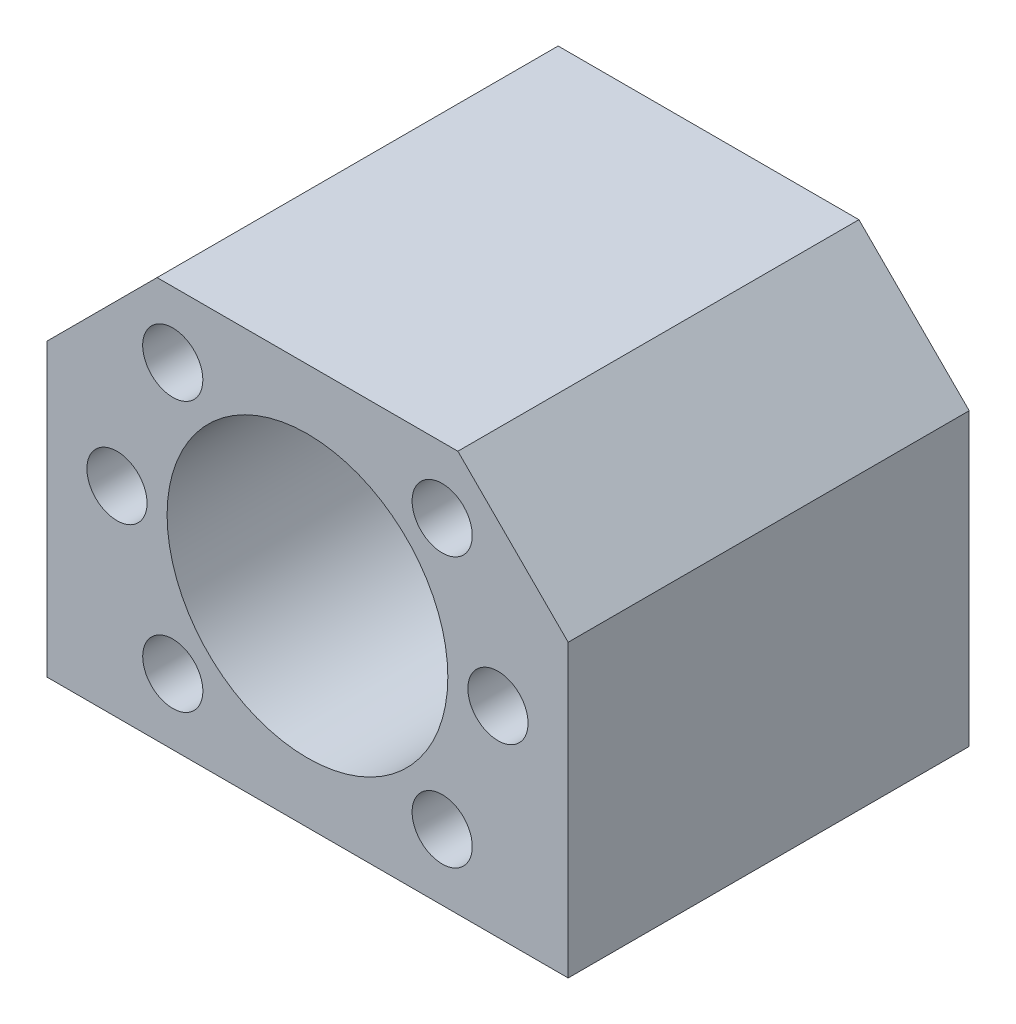
SolidWorks part; units mm, degrees
ref_plane "Plan de face" through (0, 0, 0) normal (0, 0, 1) x (1, 0, 0)
ref_plane "Plan de dessus" through (0, 0, 0) normal (0, 1, 0) x (1, 0, 0)
ref_plane "Plan de droite" through (0, 0, 0) normal (1, 0, 0) x (0, 0, -1)
sketch "Esquisse1" plane through (0, 0, 0) normal (0, 0, 1) x (1, 0, 0)
  line L1 (0, 0) -> (52, 0)
  line L2 (0, 0) -> (0, 40)
  line L3 (0, 40) -> (52, 40)
  line L4 (52, 0) -> (52, 40)
  dimension "D1" = 52
  dimension "D2" = 40
extrude "Boss.-Extru.1" add sketch "Esquisse1" along normal blind 40
sketch "Esquisse2" plane through (0, 0, 40) normal (0, 0, 1) x (1, 0, 0)
  line L0 (26, 0) -> (26, 40) construction
  line L1 (0, 0) -> (52, 0) construction
  line L2 (52, 40) -> (0, 40) construction
  circle A0 centre (26, 20) radius 14
  dimension "D1" = 28
extrude "Enlèv. mat.-Extru.1" cut sketch "Esquisse2" against normal up to vertex (40 mm away) up to point (52, 0, 0)
sketch "Esquisse3" plane through (0, 0, 40) normal (0, 0, 1) x (1, 0, 0)
  line L0 (0, 20) -> (52, 20) construction
  line L1 (0, 40) -> (0, 0) construction
  line L2 (52, 0) -> (52, 40) construction
  line L3 (26, 40) -> (26, 0) construction
  line L4 (52, 40) -> (0, 40) construction
  line L5 (0, 0) -> (52, 0) construction
  line L6 (26, 20) -> (12.565, 33.435) construction
  circle A0 centre (7, 20) radius 3
  circle A1 centre (12.565, 33.435) radius 3
  arc A2 (7, 20) -> (12.565, 33.435) centre (26, 20) cw construction
  circle A3 centre (12.565, 6.565) radius 3
  arc A4 (45, 20) -> (39.435, 33.435) centre (26, 20) ccw construction
  circle A5 centre (39.435, 6.565) radius 3
  circle A6 centre (39.435, 33.435) radius 3
  circle A7 centre (45, 20) radius 3
  dimension "D1" = 6
  dimension "D2" = 38
  dimension "D3" = 45
extrude "Enlèv. mat.-Extru.2" cut sketch "Esquisse3" against normal blind 10
chamfer "Chanfrein1" distance 11 angle 45 2 edges at (0, 40, 20) (52, 40, 20)
sketch "Esquisse4" plane through (0, 0, 0) normal (0, -1, 0) x (1, 0, 0)
  line L0 (26, 0) -> (26, 40) construction
  line L1 (0, 0) -> (52, 0) construction
  line L2 (0, 40) -> (52, 40) construction
  line L3 (0, 20) -> (52, 20) construction
  line L4 (0, 40) -> (0, 0) construction
  line L5 (52, 40) -> (52, 0) construction
  circle A0 centre (6, 32) radius 3
  circle A1 centre (6, 8) radius 3
  circle A2 centre (46, 8) radius 3
  circle A3 centre (46, 32) radius 3
  dimension "D3" = 6
  dimension "D1" = 24
  dimension "D2" = 40
extrude "Enlèv. mat.-Extru.3" cut sketch "Esquisse4" against normal blind 10
